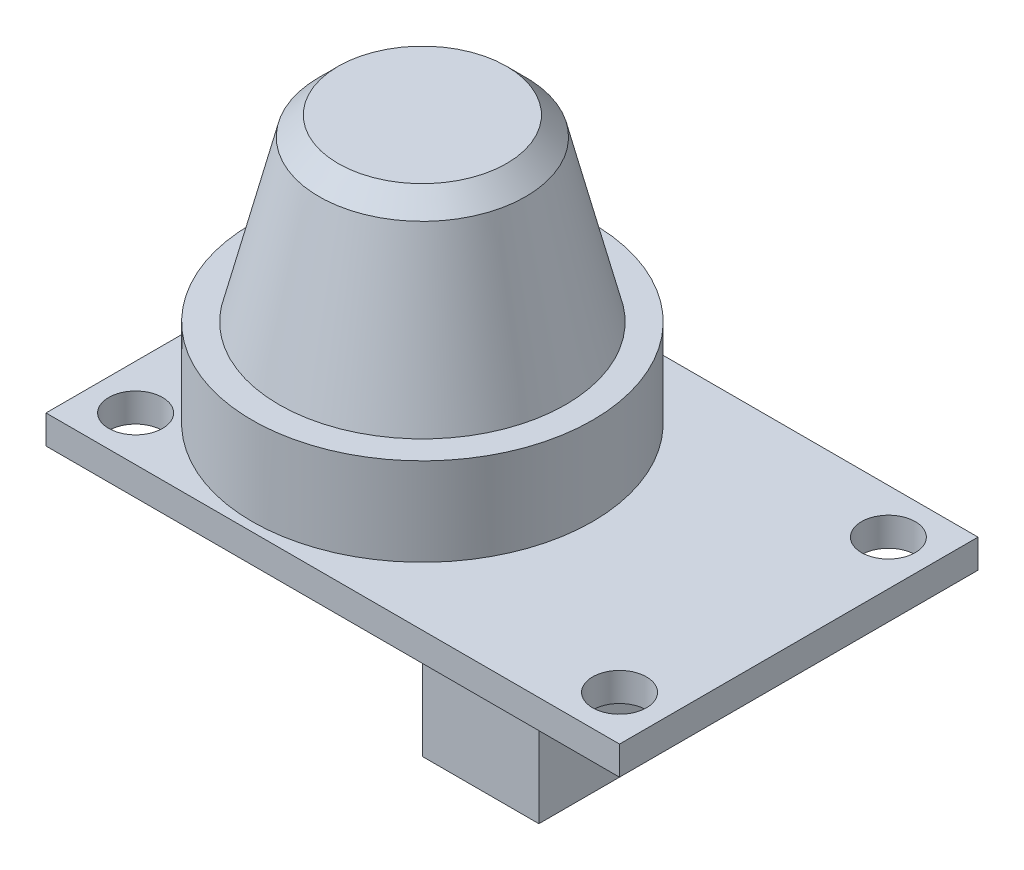
SolidWorks part; units mm, degrees
ref_plane "前视基准面" through (0, 0, 0) normal (0, 0, 1) x (1, 0, 0)
ref_plane "上视基准面" through (0, 0, 0) normal (0, 1, 0) x (1, 0, 0)
ref_plane "右视基准面" through (0, 0, 0) normal (1, 0, 0) x (0, 0, -1)
other "Configuration Table"
sketch "草图1" plane through (0, 0, 0) normal (0, 1, 0) x (1, 0, 0)
  line L1 (-16, 10) -> (16, 10)
  line L2 (-16, 10) -> (-16, -10)
  line L3 (-16, -10) -> (16, -10)
  line L4 (16, 10) -> (16, -10)
  line L5 (-16, 10) -> (16, -10) construction
  line L6 (-16, -10) -> (16, 10) construction
  circle A0 centre (-13.5, 7.5) radius 1.5
  circle A1 centre (13.5, 7.5) radius 1.5
  circle A2 centre (-13.5, -7.5) radius 1.5
  circle A3 centre (13.5, -7.5) radius 1.5
  point P0 (0, 0)
  point P14 (0, 0)
  point P15 (0, 0)
  point P16 (11.7296, 7.6101)
  point P17 (0, 0)
  point P19 (20.4088, 3.3648)
  point P20 (13.1447, 10.4403)
  dimension "D3" = 3
  dimension "D4" = 3
  dimension "D5" = 3
  dimension "D6" = 3
  dimension "D1" = 20
  dimension "D2" = 32
  dimension "D7" = 27
  dimension "D8" = 15
  dimension "D9" = 27
  dimension "D10" = 15
  dimension "D11" = 2.5
  dimension "D12" = 2.5
extrude "凸台-拉伸1" add sketch "草图1" along normal blind 1.6
sketch "草图2" plane through (0, 0, 0) normal (0, 1, 0) x (1, 0, 0)
  line L0 (-16, -10) -> (16, -10) construction
  line L1 (4.5, -9.5) -> (11, -9.5)
  line L2 (4.5, -9.5) -> (4.5, -3)
  line L3 (4.5, -3) -> (11, -3)
  line L4 (11, -9.5) -> (11, -3)
  line L5 (16, -10) -> (16, 10) construction
  dimension "D1" = 6.5
  dimension "D2" = 6.5
  dimension "D3" = 0.5
  dimension "D4" = 5
extrude "凸台-拉伸2" add sketch "草图2" against normal blind 5 from surface at 0 starting at face at (0, 0, 0)
sketch "草图3" plane through (0, 0, 0) normal (0, 1, 0) x (1, 0, 0)
  line L0 (-16, 10) -> (-16, -10) construction
  circle A0 centre (-5, 0) radius 9.5
  point P4 (0, 0)
  dimension "D1" = 19
  dimension "D2" = 11
extrude "凸台-拉伸3" add sketch "草图3" along normal blind 16.5
sketch "草图4" plane through (0, 0, 0) normal (0, 0, 1) x (1, 0, 0)
  line L0 (4.5, 16.5) -> (-14.5, 16.5) construction
  line L1 (4.5, 16.5) -> (-14.5, 16.5) construction
  line L2 (-5, -983.5) -> (-5, 49016.5) construction
  line L3 (0.7667, 15.4333) -> (3, 6.5)
  line L4 (3, 6.5) -> (4.5, 6.5)
  line L5 (4.5, 6.5) -> (4.5, 16.5)
  line L6 (4.5, 16.5) -> (0.5, 16.5)
  line L7 (0.7667, 15.4333) -> (-0.3, 16.5)
  line L8 (-0.3, 16.5) -> (0.5, 16.5)
  line L9 (-0.3, 16.5) -> (0.5, 16.5)
  point P2 (-5, 16.5)
  dimension "D1" = 10
  dimension "D2" = 4
  dimension "D3" = 1.5
  dimension "D4" = 0.8
  dimension "D5" = 45
  dimension "D6" = 8.9333
revolve "切除-旋转2" cut sketch "草图4" angle 360 about L2
